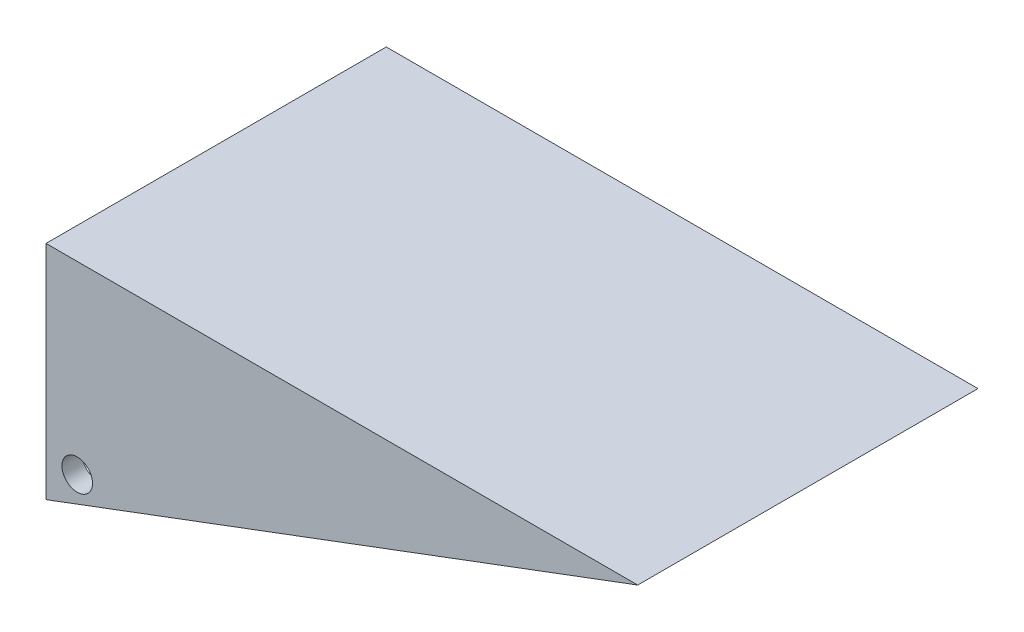
SolidWorks part; units mm, degrees
ref_plane "Front Plane" through (0, 0, 0) normal (0, 0, 1) x (1, 0, 0)
ref_plane "Top Plane" through (0, 0, 0) normal (0, 1, 0) x (1, 0, 0)
ref_plane "Right Plane" through (0, 0, 0) normal (1, 0, 0) x (0, 0, -1)
sketch "Sketch1" plane through (0, 0, 0) normal (0, 0, 1) x (1, 0, 0)
  line L0 (0, 0) -> (0, 15)
  line L1 (0, 15) -> (40, 15)
  line L2 (40, 15) -> (0, 0)
  dimension "D1" = 40
  dimension "D2" = 15
extrude "Boss-Extrude2" add sketch "Sketch1" along normal blind 22 and the other way blind 1 contours L1 L2 L0
sketch "Sketch2" plane through (0, 0, 0) normal (-1, 0, 0) x (0, 0, 1)
  line L1 (0.3876, 13.5352) -> (20.6372, 13.5352)
  line L2 (0.3876, 13.5352) -> (0.3876, -0.1958)
  line L3 (0.3876, -0.1958) -> (20.6372, -0.1958)
  line L4 (20.6372, 13.5352) -> (20.6372, -0.1958)
extrude "Cut-Extrude1" cut sketch "Sketch2" against normal blind 43
sketch "Sketch3" plane through (0, 0, 22) normal (0, 0, 1) x (1, 0, 0)
  line L0 (2.1115, 15) -> (2.1115, 2.5214)
  line L1 (0, 15) -> (40, 15) construction
  circle A0 centre (2.1115, 2.5214) radius 1.0345
extrude "Cut-Extrude2" cut sketch "Sketch3" against normal blind 43 contours A0
